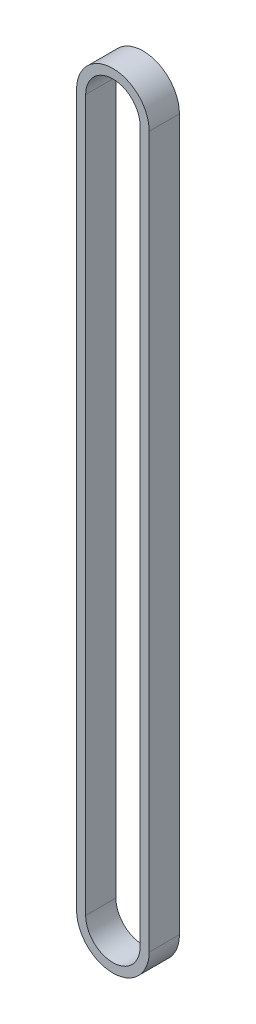
SolidWorks part; units mm, degrees
ref_plane "前视基准面" through (0, 0, 0) normal (0, 0, 1) x (1, 0, 0)
ref_plane "上视基准面" through (0, 0, 0) normal (0, 1, 0) x (1, 0, 0)
ref_plane "右视基准面" through (0, 0, 0) normal (1, 0, 0) x (0, 0, -1)
sketch "草图1" plane through (0, 0, 0) normal (0, 0, 1) x (1, 0, 0)
  line L0 (0, 0) -> (0, -235) construction
  line L1 (12, 0) -> (12, -235)
  line L2 (-12, 0) -> (-12, -235)
  line L3 (0, 0) -> (0, -235) construction
  line L4 (9, 0) -> (9, -235)
  line L5 (-9, 0) -> (-9, -235)
  arc A0 (12, 0) -> (-12, 0) centre (0, 0) ccw
  arc A1 (-12, -235) -> (12, -235) centre (0, -235) ccw
  arc A2 (9, 0) -> (-9, 0) centre (0, 0) ccw
  arc A3 (-9, -235) -> (9, -235) centre (0, -235) ccw
  point P3 (0, -117.5)
  point P10 (0, -117.5)
  dimension "D3" = 9
  dimension "D1" = 235
extrude "凸台-拉伸1" add sketch "草图1" along normal blind 10
